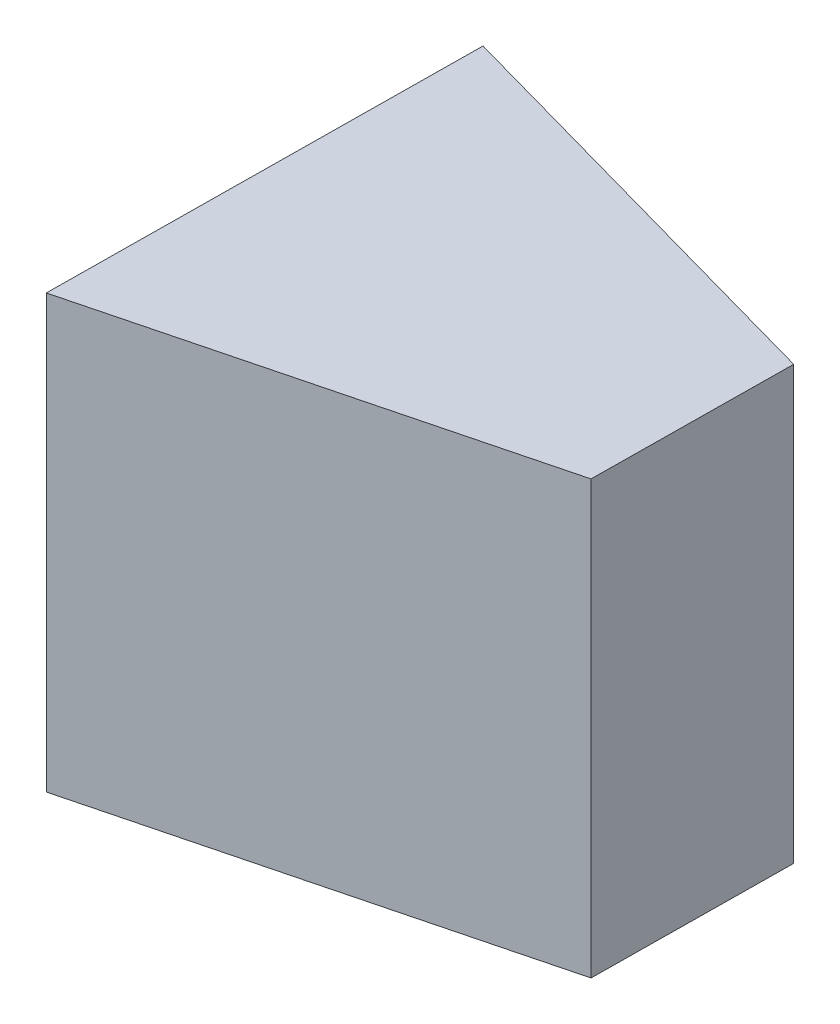
SolidWorks part; units mm, degrees
ref_plane "Plan de face" through (0, 0, 0) normal (0, 0, 1) x (1, 0, 0)
ref_plane "Plan de dessus" through (0, 0, 0) normal (0, 1, 0) x (1, 0, 0)
ref_plane "Plan de droite" through (0, 0, 0) normal (1, 0, 0) x (0, 0, -1)
sketch "Esquisse1" plane through (0, 0, 0) normal (0, 1, 0) x (1, 0, 0)
  line L1 (25.2596, 24.7377) -> (-24.7377, 25.2596)
  line L2 (-24.7377, 25.2596) -> (-25.2596, -24.7377)
  line L3 (-25.2596, -24.7377) -> (24.7377, -25.2596)
  line L4 (24.7377, -25.2596) -> (25.2596, 24.7377)
  circle A0 centre (0, 0) radius 25 construction
  point P1 (-52.2566, 51.1769)
extrude "Boss.-Extru.1" add sketch "Esquisse1" along normal blind 50
draft "Dépouille7" type of draft neutral plane draft angle 15 faces to draft 2 face at (0.2609, 25, -24.9986) face at (-0.2609, 25, 24.9986) neutral plane through (-24.7377, 50, -25.2596) neutral plane normal (-0.9999, 0, -0.0104) parameters "D1"=15
draft "Dépouille8" type of draft neutral plane draft angle 15 faces to draft 2 face at (0.3309, 25, -31.697) face at (-0.3309, 25, 31.697) neutral plane through (-24.7377, 50, -25.2596) neutral plane normal (-0.9999, 0, -0.0104) reverse direction yes parameters "D1"=15
